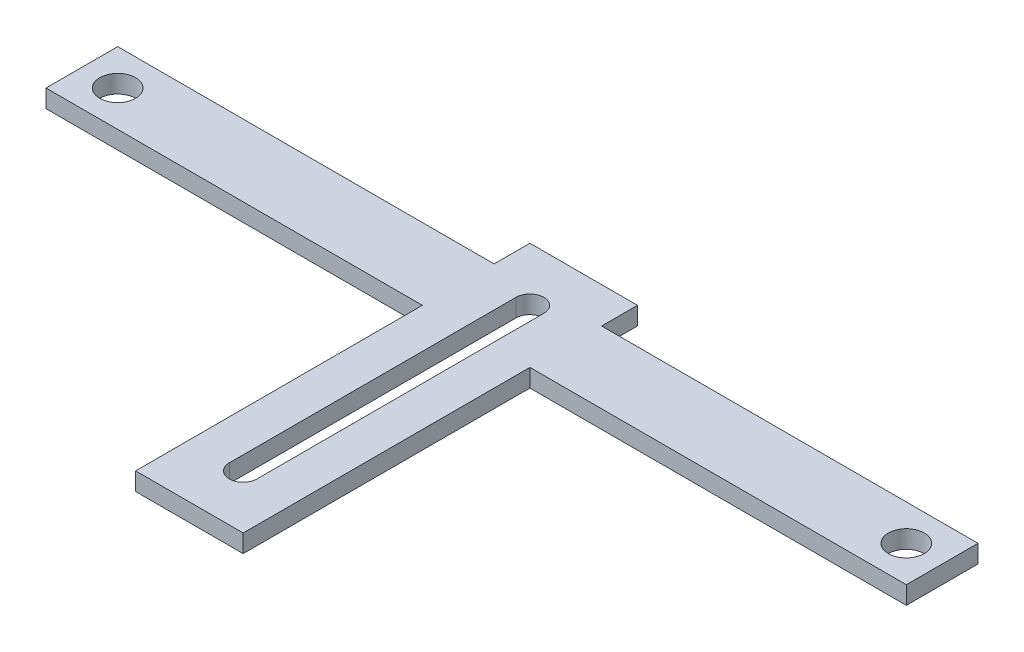
SolidWorks part; units mm, degrees
ref_plane "Front" through (0, 0, 0) normal (0, 0, 1) x (1, 0, 0)
ref_plane "Top" through (0, 0, 0) normal (0, 1, 0) x (1, 0, 0)
ref_plane "Right" through (0, 0, 0) normal (1, 0, 0) x (0, 0, -1)
sketch "Sketch1" plane through (0, 0, 0) normal (0, 1, 0) x (1, 0, 0)
  line L0 (-139.7, 0) -> (0, 0) construction
  line L1 (-152.4, -12.7) -> (152.4, -12.7)
  line L2 (-152.4, -12.7) -> (-152.4, 12.7)
  line L3 (-152.4, 12.7) -> (152.4, 12.7)
  line L4 (152.4, -12.7) -> (152.4, 12.7)
  line L5 (-152.4, -12.7) -> (152.4, 12.7) construction
  line L6 (-152.4, 12.7) -> (152.4, -12.7) construction
  line L7 (0, 0) -> (139.7, 0) construction
  circle A0 centre (-139.7, 0) radius 6.35
  circle A1 centre (139.7, 0) radius 6.35
  point P0 (0, 0)
  dimension "D3" = 279.4
  dimension "D1" = 304.8
  dimension "D2" = 25.4
extrude "Boss-Extrude1" add sketch "Sketch1" along normal blind 6.35
sketch "Sketch2" plane through (0, 6.35, 0) normal (0, 1, 0) x (1, 0, 0)
  line L0 (-152.4, -12.7) -> (152.4, -12.7) construction
  line L2 (-19.05, -12.7) -> (-19.05, -114.3)
  line L3 (-19.05, -114.3) -> (19.05, -114.3)
  line L4 (19.05, -12.7) -> (19.05, -114.3)
  line L5 (-19.05, -12.7) -> (19.05, -114.3) construction
  line L6 (-19.05, -114.3) -> (19.05, -12.7) construction
  line L7 (-152.4, -12.7) -> (-19.05, -12.7) construction
  line L8 (19.05, -12.7) -> (152.4, -12.7) construction
  line L11 (-19.05, -12.7) -> (-19.05, 25.4)
  line L12 (-19.05, 25.4) -> (19.05, 25.4)
  line L13 (19.05, -12.7) -> (19.05, 25.4)
  line L14 (-19.05, -12.7) -> (19.05, 25.4) construction
  line L15 (-19.05, 25.4) -> (19.05, -12.7) construction
  point P4 (0, -63.5)
  point P13 (0, 6.35)
  dimension "D1" = 101.6
  dimension "D2" = 38.1
  dimension "D3" = 38.1
extrude "Boss-Extrude2" add sketch "Sketch2" against normal up to surface (6.35 mm away) up to face at (-139.7, 0, 6.35)
sketch "Sketch3" plane through (0, 6.35, 0) normal (0, 1, 0) x (1, 0, 0)
  line L0 (0, -95.25) -> (0, 6.35) construction
  line L1 (-4.9229, -95.25) -> (-4.9229, 6.35)
  line L2 (4.9229, -95.25) -> (4.9229, 6.35)
  line L3 (-19.05, -114.3) -> (19.05, -114.3) construction
  line L4 (19.05, 25.4) -> (-19.05, 25.4) construction
  arc A0 (-4.9229, -95.25) -> (4.9229, -95.25) centre (0, -95.25) ccw
  arc A1 (4.9229, 6.35) -> (-4.9229, 6.35) centre (0, 6.35) ccw
  point P3 (0, -44.45)
  point P8 (0, -16.9541)
  point P9 (0, -174.287)
  point P12 (0, -114.3)
  point P13 (0, 17.312)
  dimension "D1" = 19.05
  dimension "D2" = 19.05
extrude "Cut-Extrude1" cut sketch "Sketch3" against normal up to next
